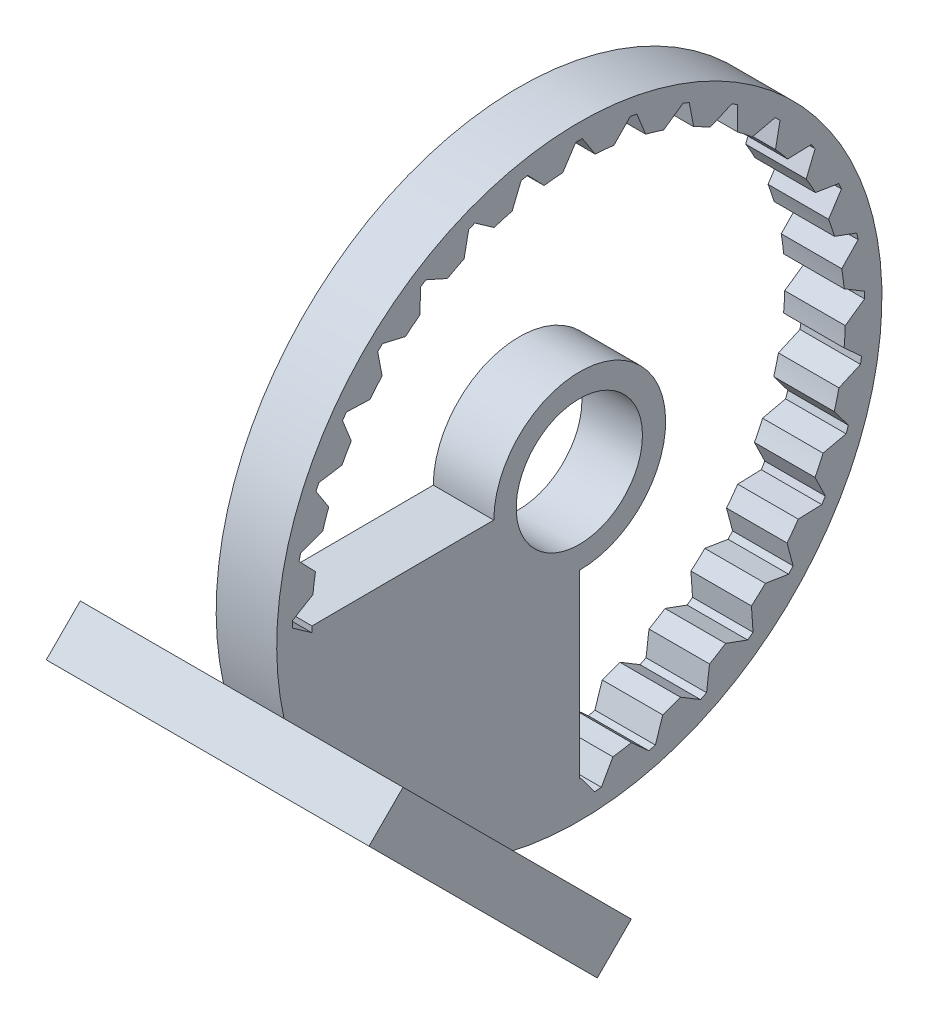
SolidWorks part; units mm, degrees
ref_plane "Front Plane" through (0, 0, 0) normal (1, 0, 0) x (0, 1, 0)
ref_plane "Top Plane" through (0, 0, 0) normal (0, 0, 1) x (0, 1, 0)
ref_plane "Right Plane" through (0, 0, 0) normal (0, 1, 0) x (-1, 0, 0)
sketch "Sketch1" plane through (0, 0, 0) normal (1, 0, 0) x (0, 1, 0)
  circle A0 centre (0, 0) radius 50
  dimension "D1" = 100
extrude "Boss-Extrude2" add sketch "Sketch1" along normal blind 10
sketch "Sketch7" plane through (10, 0, 0) normal (1, 0, 0) x (0, 1, 0)
  circle A0 centre (0, 0) radius 10.4309
extrude "Cut-Extrude5" cut sketch "Sketch7" against normal blind 10
sketch "Sketch10" plane through (10, 0, 0) normal (1, 0, 0) x (0, 1, 0)
  line L0 (-43.9544, 0) -> (-14.1328, 0)
  line L1 (0, 44.2137) -> (0.1297, 14.1328)
  arc A0 (-43.9544, 0) -> (0, 44.2137) centre (0.1297, 0.1297) ccw
  arc A1 (-14.1328, 0) -> (0.1297, 14.1328) centre (0.0648, -0.0648) ccw
extrude "Cut-Extrude8" cut sketch "Sketch10" against normal through all
sketch "Sketch12" plane through (10, 0, 0) normal (1, 0, 0) x (0, 1, 0)
  line L0 (47.4003, 0) -> (47.4003, 0.608)
  line L1 (47.4003, 0.608) -> (44.1364, 2.7427)
  line L2 (44.1364, 2.7427) -> (44.1284, -2.6151)
  line L3 (44.1284, -2.6151) -> (47.4003, -0.5006)
  line L4 (47.4003, -0.5006) -> (47.4003, 0)
  arc A0 (-43.9544, 0) -> (0, 44.2137) centre (0.1297, 0.1297) ccw construction
extrude "Cut-Extrude9" cut sketch "Sketch12" against normal through all
pattern_circular "CirPattern3" count 9 every 11 about axis through (0, 0.1297, 0.1297) along (1, 0, 0) of "Cut-Extrude9"
pattern_circular "CirPattern4" count 17 every 11 about axis through (0, 0.1297, 0.1297) along (1, 0, 0) of "Cut-Extrude9"
scale "Scale3" scale about origin uniform scaling yes scale factor 0.75
sketch "Sketch15" plane through (7.5, 0, 0) normal (1, 0, 0) x (0, 1, 0)
  line L0 (-12.1728, 41.0593) -> (-7.9565, 36.843)
  line L1 (-7.9565, 36.843) -> (-36.2407, 8.5587)
  line L2 (-36.2407, 8.5587) -> (-40.457, 12.775)
  line L3 (-40.457, 12.775) -> (-12.1728, 41.0593)
  dimension "D1" = 40
extrude "Boss-Extrude3" add sketch "Sketch15" along normal blind 15
sketch "Sketch20" plane through (7.5, 0, 0) normal (-1, 0, 0) x (0, -1, 0)
  line L0 (7.9565, 36.843) -> (12.1728, 41.0593)
  line L1 (12.1728, 41.0593) -> (40.457, 12.775)
  line L2 (40.457, 12.775) -> (36.2407, 8.5587)
  line L3 (36.2407, 8.5587) -> (7.9565, 36.843)
  line L4 (7.9565, 36.843) -> (12.1728, 41.0593) construction
  line L5 (12.1728, 41.0593) -> (40.457, 12.775) construction
  line L6 (40.457, 12.775) -> (36.4585, 8.7765) construction
extrude "Boss-Extrude6" add sketch "Sketch20" along normal blind 25
sketch "Sketch19" plane through (0, -26.616, 26.616) normal (0, -0.7071, 0.7071) x (1, 0, 0)
  line L0 (22.5, 20.4259) -> (-17.5, 20.4259) construction
  line L1 (22.5, 20.4259) -> (22.5, -19.5741) construction
  line L3 (-17.5, -19.5741) -> (-17.5, 20.4259) construction
  line L4 (22.5, -19.5741) -> (-17.5, -19.5741) construction
  circle A0 centre (-14.5, -16.5741) radius 1.5
  circle A4 centre (-14.5, 17.4259) radius 1.5
  circle A6 centre (-11.5, 14.4259) radius 1.5
  circle A7 centre (-11.5, -13.5741) radius 1.5
  circle A8 centre (19.5, 17.4259) radius 1.5
  circle A9 centre (16.5, 14.4259) radius 1.5
  circle A10 centre (16.5, -13.5741) radius 1.5
  circle A11 centre (19.5, -16.5741) radius 1.5
  dimension "D1" = 3
  dimension "D2" = 34
  dimension "D3" = 28
  dimension "D4" = 34
  dimension "D5" = 28
  dimension "D6" = 28
  dimension "D7" = 34
  dimension "D8" = 34
  dimension "D9" = 28
  dimension "D10" = 3
  dimension "D11" = 3
  dimension "D12" = 6
  dimension "D13" = 6
  dimension "D14" = 3
  dimension "D15" = 3
  dimension "D16" = 6
  dimension "D17" = 6
  dimension "D18" = 6
extrude "Cut-Extrude10" cut sketch "Sketch19" against normal blind 2.5
